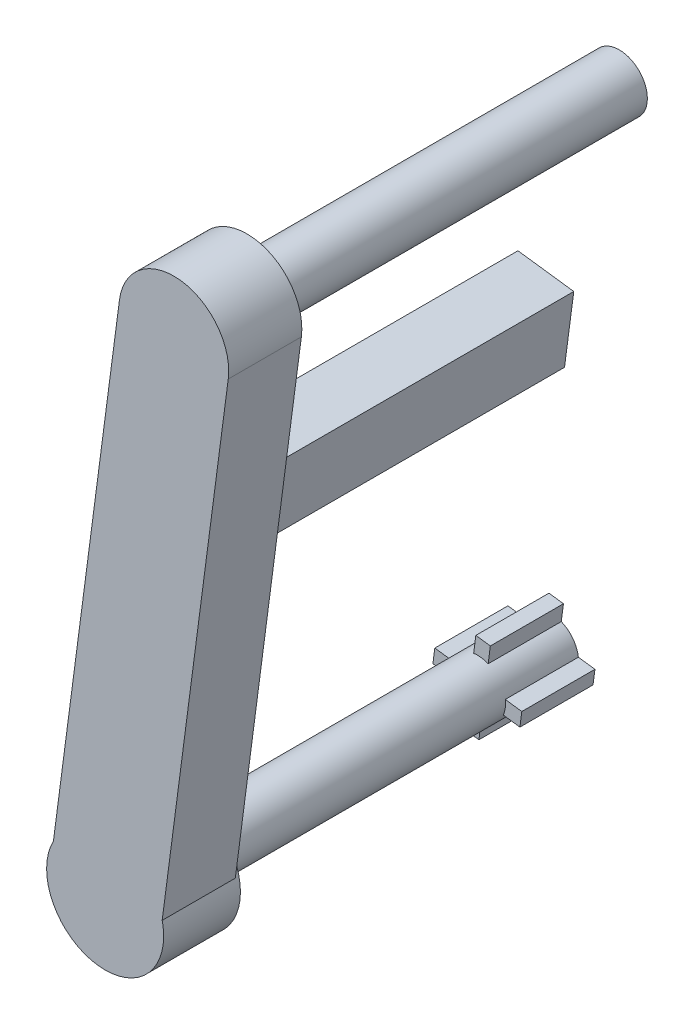
SolidWorks part; units mm, degrees
ref_plane "Piano frontale" through (0, 0, 0) normal (0, 0, 1) x (1, 0, 0)
ref_plane "Piano superiore" through (0, 0, 0) normal (0, 1, 0) x (1, 0, 0)
ref_plane "Piano destro" through (0, 0, 0) normal (1, 0, 0) x (0, 0, -1)
other "Graphic1"
other "Graphic (Closed) -1"
sketch "Sketch1" plane through (0, 0, 0) normal (0, 0, 1) x (1, 0, 0)
  circle A0 centre (0, 0) radius 20.1563
  circle A1 centre (0, 0) radius 8
  dimension "D1" = 16
extrude "Boss-Extrude1" add sketch "Sketch1" against normal blind 10.5 contours A1
sketch "Sketch2" plane through (0, 0, -10.5) normal (0, 0, -1) x (-1, 0, 0)
  circle A0 centre (0, 0) radius 3.85
  dimension "D1" = 7.7
extrude "Boss-Extrude2" add sketch "Sketch2" along normal blind 60
sketch "Sketch3" plane through (0, 0, -70.5) normal (0, 0, -1) x (-1, 0, 0)
  line L0 (-6.0792, 0.2083) -> (-1.122, 0.8609)
  line L1 (-1.7746, 5.8181) -> (0.2083, 6.0792)
  line L4 (-0.7832, 5.9487) -> (0, 0) construction
  line L5 (5.8181, 1.7746) -> (6.0792, -0.2083)
  line L6 (1.7746, -5.8181) -> (-0.2083, -6.0792)
  line L7 (-5.8181, -1.7746) -> (-6.0792, 0.2083)
  line L8 (-1.122, 0.8609) -> (-1.7746, 5.8181)
  line L9 (0.2083, 6.0792) -> (0.8609, 1.122)
  line L10 (0.8609, 1.122) -> (5.8181, 1.7746)
  line L11 (6.0792, -0.2083) -> (1.122, -0.8609)
  line L12 (1.122, -0.8609) -> (1.7746, -5.8181)
  line L13 (-0.2083, -6.0792) -> (-0.8609, -1.122)
  line L14 (-0.8609, -1.122) -> (-5.8181, -1.7746)
  point P16 (0, 0)
  dimension "D1" = 1
  dimension "D2" = 6
  dimension "D3" = 4
extrude "Boss-Extrude3" add sketch "Sketch3" against normal blind 10 from offset 9.6 offset against normal yes
sketch "Sketch6" plane through (0, 0, -70.5) normal (0, 0, -1) x (-1, 0, 0)
  circle A1 centre (0, 0) radius 3.85
  circle A2 centre (0, 0) radius 3.85
  dimension "D1" = 0
extrude "Cut-Extrude1" cut sketch "Sketch6" against normal up to surface (9.6 mm away) up to face at (4.8501, -0.6385, -60.9)
sketch "Sketch7" plane through (0, 0, 0) normal (0, 0, 1) x (1, 0, 0)
  line L0 (0, 0) -> (9.3979, 71.384) construction
  line L1 (1.962, 72.363) -> (-7.0725, 3.739)
  line L2 (16.8337, 70.4051) -> (7.7992, 1.7811)
  line L3 (7.7992, 1.7811) -> (-7.0725, 3.739)
  arc A0 (16.8337, 70.4051) -> (1.962, 72.363) centre (9.3979, 71.384) ccw
  dimension "D2" = 7.5
  dimension "D1" = 72
  dimension "D3" = 15
extrude "Boss-Extrude4" add sketch "Sketch7" against normal blind 10
sketch "Sketch8" plane through (0, 0, -10) normal (0, 0, -1) x (-1, 0, 0)
  circle A0 centre (-9.3979, 71.384) radius 4.5
  dimension "D1" = 9
extrude "Boss-Extrude5" add sketch "Sketch8" along normal blind 0.5
sketch "Sketch9" plane through (0, 0, -10.5) normal (0, 0, -1) x (-1, 0, 0)
  circle A0 centre (-9.3979, 71.384) radius 3.85
  dimension "D1" = 7.7
extrude "Boss-Extrude6" add sketch "Sketch9" along normal up to surface (50.4 mm away) up to face at (0, 0, -60.9)
sketch "Sketch10" plane through (0, 0, 0) normal (0, 0, 1) x (1, 0, 0)
  circle A0 centre (0, 0) radius 22.5
  dimension "D1" = 45
sketch "Sketch11" plane through (0, 0, -10) normal (0, 0, -1) x (-1, 0, 0)
  line L0 (-2.9513, 51.9089) -> (-10.5848, 50.9039)
  line L1 (-10.5848, 50.9039) -> (-9.3187, 41.2869)
  line L2 (-9.3187, 41.2869) -> (-1.6852, 42.2918)
  line L3 (-1.6852, 42.2918) -> (-2.9513, 51.9089)
  line L4 (-2.8222, 52.0772) -> (-10.7531, 51.033)
  line L5 (-1.5169, 42.1627) -> (-2.8222, 52.0772)
  line L6 (-9.4479, 41.1186) -> (-1.5169, 42.1627)
  line L7 (-10.7531, 51.033) -> (-9.4479, 41.1186)
  line L8 (-2.8222, 52.0772) -> (-10.7531, 51.033) construction
  line L9 (-1.5169, 42.1627) -> (-2.8222, 52.0772) construction
  line L10 (-9.4479, 41.1186) -> (-1.5169, 42.1627) construction
  line L11 (-10.7531, 51.033) -> (-9.4479, 41.1186) construction
  dimension "D1" = 0
  dimension "D2" = 0.15
extrude "Boss-Extrude7" add sketch "Sketch11" along normal up to surface (43.5 mm away)
sketch "Sketch12" plane through (0, 0, -53.5) normal (0, 0, -1) x (-1, 0, 0)
  circle A0 centre (-6.135, 46.5979) radius 1.75 construction
  circle A1 centre (-6.135, 46.5979) radius 1.75
extrude "Cut-Extrude2" cut sketch "Sketch12" against normal blind 10
